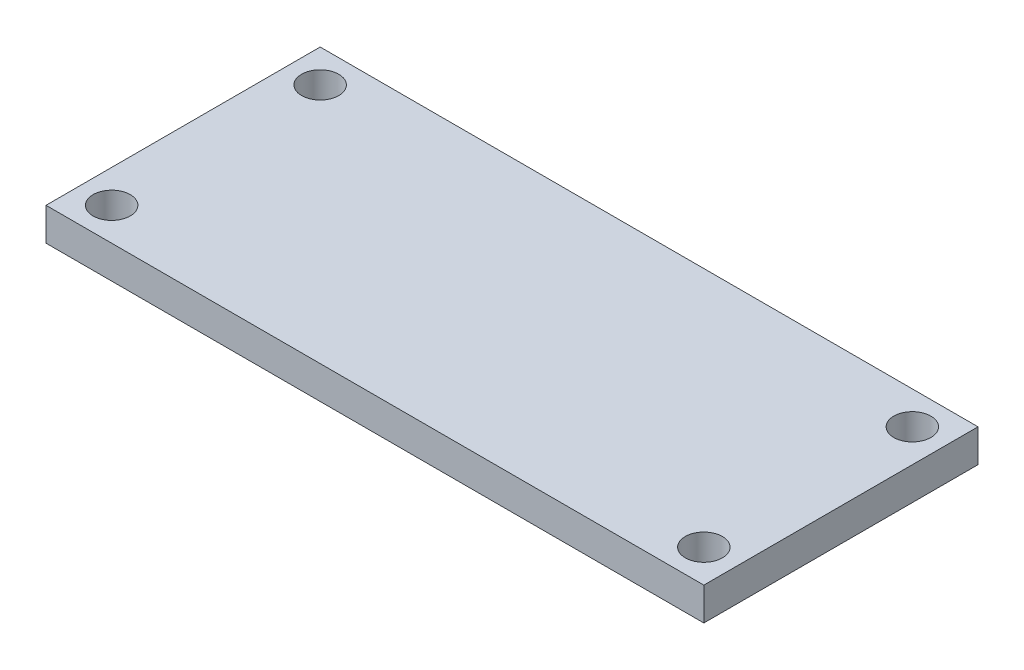
SolidWorks part; units mm, degrees
ref_plane "Front Plane" through (0, 0, 0) normal (0, 0, 1) x (1, 0, 0)
ref_plane "Top Plane" through (0, 0, 0) normal (0, 1, 0) x (1, 0, 0)
ref_plane "Right Plane" through (0, 0, 0) normal (1, 0, 0) x (0, 0, -1)
sketch "Sketch1" plane through (0, 0, 0) normal (0, 1, 0) x (1, 0, 0)
  line L0 (2, -2) -> (38.07, -2)
  line L1 (2, -2) -> (2, -14.7)
  line L2 (2, -14.7) -> (38.07, -14.7)
  line L3 (38.07, -2) -> (38.07, -14.7)
  line L4 (0, 0) -> (40.07, 0)
  line L5 (0, 0) -> (0, -16.7)
  line L6 (0, -16.7) -> (40.07, -16.7)
  line L7 (40.07, 0) -> (40.07, -16.7)
  circle A0 centre (2, -2) radius 1.1303
  circle A1 centre (38.07, -2) radius 1.1303
  circle A2 centre (38.07, -14.7) radius 1.1303
  circle A3 centre (2, -14.7) radius 1.1303
  circle A4 centre (2, -2) radius 1.7907 construction
  circle A5 centre (2, -14.7) radius 1.7907 construction
  circle A6 centre (38.07, -14.7) radius 1.7907 construction
  circle A7 centre (38.07, -2) radius 1.7907 construction
  point P4 (1.8082, -2)
  point P5 (44.5702, -19.3418)
  point P21 (40.5313, -17.0402)
  dimension "D3" = 2.2606
  dimension "D1" = 3.5814
  dimension "D2" = 36.07
  dimension "D4" = 12.7
  dimension "D5" = 2
  dimension "D6" = 2
  dimension "D7" = 2
  dimension "D8" = 2
extrude "Boss-Extrude1" add sketch "Sketch1" along normal blind 2 contours L7 L4 L5 L6 A3 L1 A0 L0 A1 L3 A2 L2 | A3 L2 A2 L3 A1 L0 A0 L1
equation "\"D7@Sketch1\"=\"D5@Sketch1\""
equation "\"D8@Sketch1\"=\"D5@Sketch1\""
equation "\"D6@Sketch1\"=\"D5@Sketch1\""
